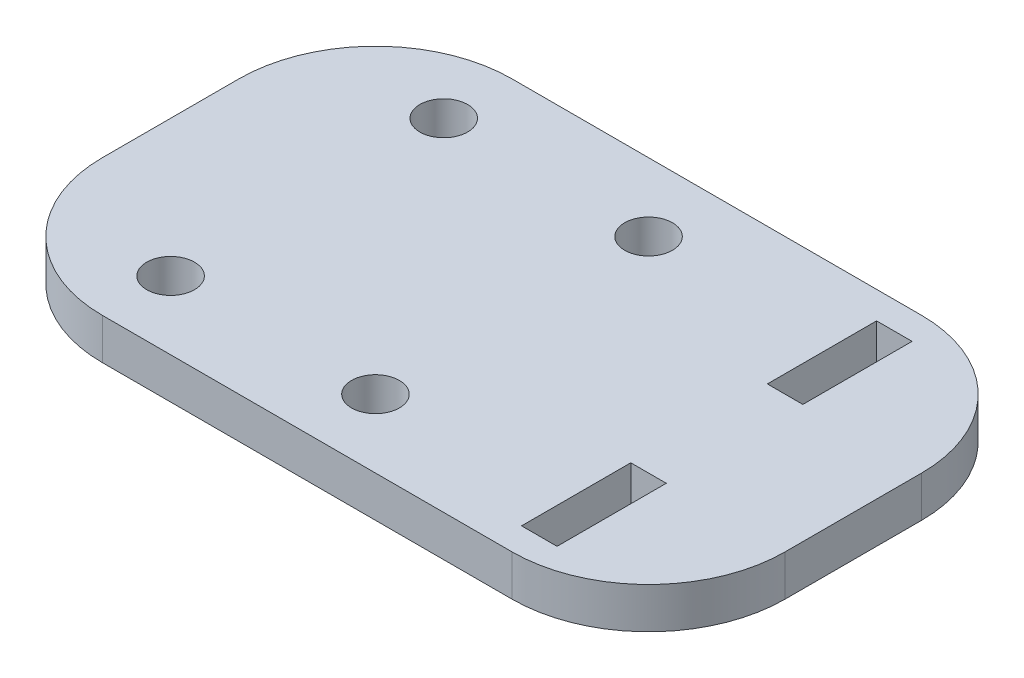
SolidWorks part; units mm, degrees
ref_plane "Front Plane" through (0, 0, 0) normal (0, 0, 1) x (1, 0, 0)
ref_plane "Top Plane" through (0, 0, 0) normal (0, 1, 0) x (1, 0, 0)
ref_plane "Right Plane" through (0, 0, 0) normal (1, 0, 0) x (0, 0, -1)
sketch "Sketch1" plane through (0, 0, 0) normal (0, 1, 0) x (1, 0, 0)
  line L0 (-33.6667, 0) -> (41.1667, 0) construction
  line L1 (-25, 15) -> (25, 15)
  line L2 (-25, 15) -> (-25, -15)
  line L3 (25, 15) -> (25, -15)
  line L4 (-25, -15) -> (25, -15)
  line L5 (15, 10) -> (15, -10) construction
  line L6 (0, 25.5) -> (0, -30.6667) construction
  line L7 (16.3, -5) -> (13.7, -5)
  line L8 (16.3, 13) -> (13.7, 13)
  line L9 (16.3, 13) -> (16.3, 5)
  line L10 (16.3, 5) -> (13.7, 5)
  line L11 (13.7, 13) -> (13.7, 5)
  line L12 (16.3, -13) -> (13.7, -13)
  line L13 (16.3, -13) -> (16.3, -5)
  line L14 (13.7, -13) -> (13.7, -5)
  circle A0 centre (-15, 10) radius 1.75
  circle A1 centre (0, 10) radius 1.75
  circle A2 centre (-15, -10) radius 1.75
  circle A3 centre (0, -10) radius 1.75
  point P7 (-16.4, 0)
  point P11 (-23.122, 0)
  point P16 (-16.4, 0)
  point P17 (-11.7, 0)
  dimension "D5" = 2.6
  dimension "D6" = 1.3
  dimension "D9" = 3.5
  dimension "D11" = 10
  dimension "D12" = 3.5
  dimension "D1" = 25
  dimension "D2" = 25
  dimension "D3" = 8.6
  dimension "D4" = 15
  dimension "D7" = 8
  dimension "D8" = 5
  dimension "D10" = 5
extrude "Boss-Extrude2" add sketch "Sketch1" along normal blind 3
fillet "Fillet1" radius 10 4 edges at (-25, 1.5, -15) (-25, 1.5, 15) (25, 1.5, -15) (25, 1.5, 15)
